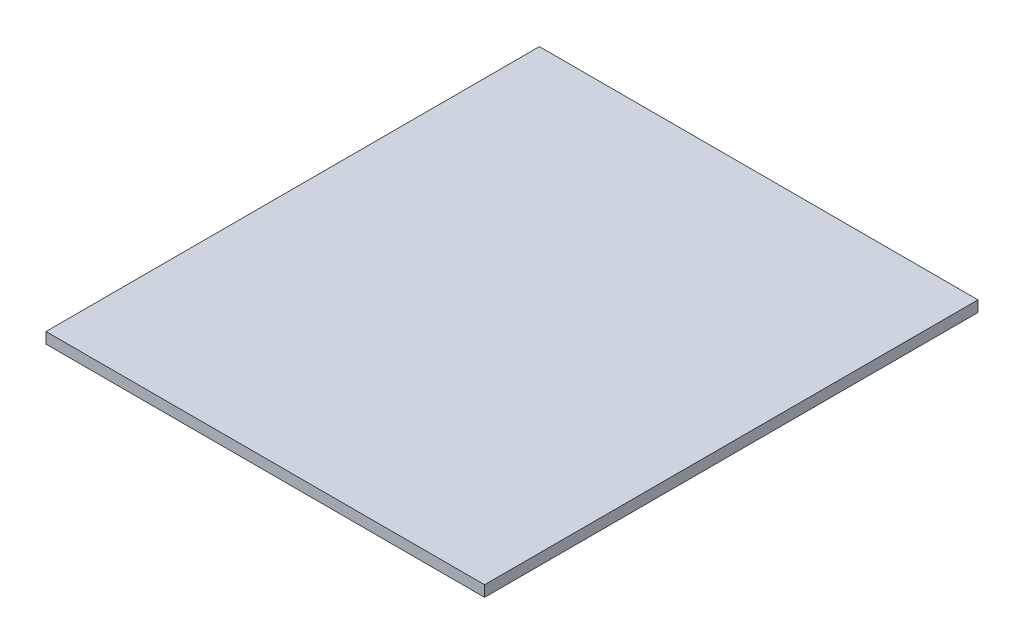
SolidWorks part; units mm, degrees
material "Balsa"
ref_plane "Plan de face" through (0, 0, 0) normal (0, 0, 1) x (1, 0, 0)
ref_plane "Plan de dessus" through (0, 0, 0) normal (0, 1, 0) x (1, 0, 0)
ref_plane "Plan de droite" through (0, 0, 0) normal (1, 0, 0) x (0, 0, -1)
sketch "Esquisse1" plane through (0, 0, 0) normal (0, 1, 0) x (1, 0, 0)
  line L1 (0, 0) -> (-400, 0)
  line L2 (0, 0) -> (0, 450)
  line L3 (0, 450) -> (-400, 450)
  line L4 (-400, 0) -> (-400, 450)
  dimension "D1" = 400
  dimension "D2" = 450
extrude "Boss.-Extru.1" add sketch "Esquisse1" along normal blind 10
